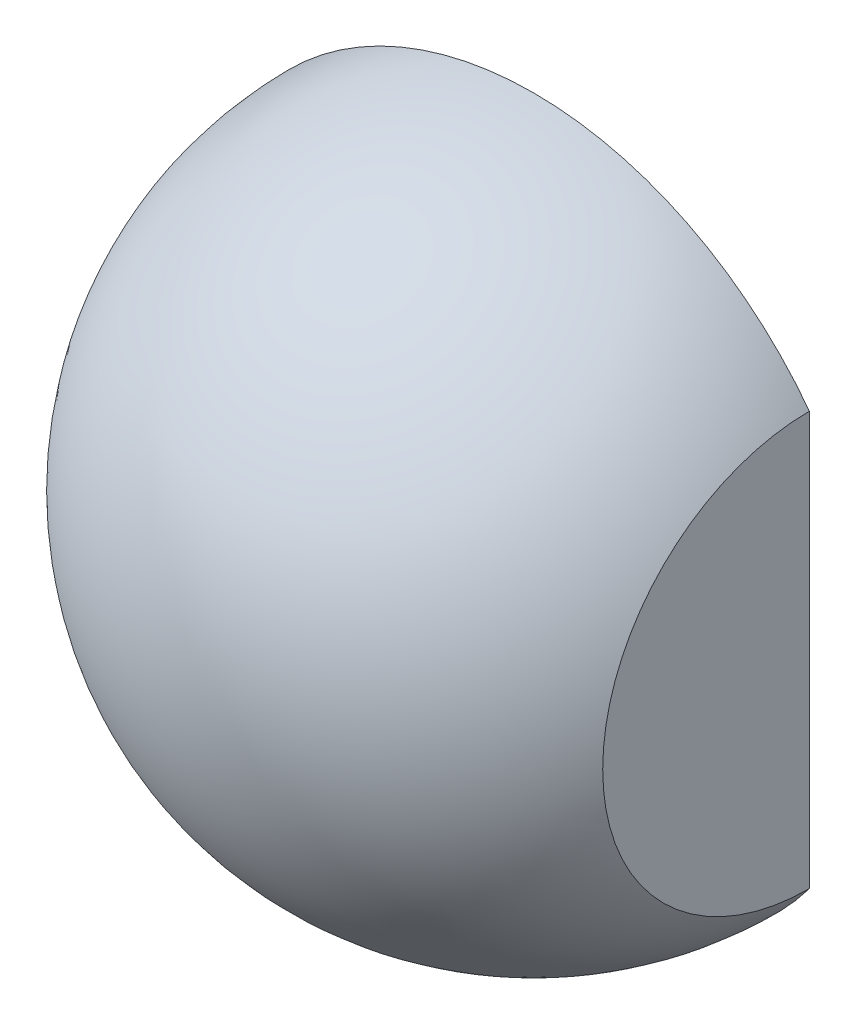
SolidWorks part; units mm, degrees
ref_plane "Front Plane" through (0, 0, 0) normal (0, 0, 1) x (1, 0, 0)
ref_plane "Top Plane" through (0, 0, 0) normal (0, 1, 0) x (1, 0, 0)
ref_plane "Right Plane" through (0, 0, 0) normal (1, 0, 0) x (0, 0, -1)
sketch "Sketch2" plane through (0, 0, 0) normal (0, 0, 1) x (1, 0, 0)
  line L0 (0, 0) -> (0, 30)
  arc A0 (0, 30) -> (0, 0) centre (0, 15) ccw
  dimension "D1" = 30
revolve "Revolve1" add sketch "Sketch2" angle 180 about L0
sketch "Sketch3" plane through (0, 0, 0) normal (0, 0, -1) x (-1, 0, 0)
  line L1 (-12, 34.7081) -> (12, 34.7081)
  line L2 (-12, 34.7081) -> (-12, -4.2692)
  line L3 (-12, -4.2692) -> (12, -4.2692)
  line L4 (12, 34.7081) -> (12, -4.2692)
  line L5 (-28.5307, 39.7997) -> (28.0917, 39.7997)
  line L6 (-28.5307, 39.7997) -> (-28.5307, -12.8723)
  line L7 (-28.5307, -12.8723) -> (28.0917, -12.8723)
  line L8 (28.0917, 39.7997) -> (28.0917, -12.8723)
  dimension "D1" = 12
  dimension "D2" = 12
extrude "Cut-Extrude1" cut sketch "Sketch3" against normal blind 10
sketch "Sketch4" plane through (0, 0, 0) normal (0, 0, -1) x (-1, 0, 0)
  line L0 (0, 0) -> (0, 30) construction
  arc A0 (12, 24) -> (-12, 24) centre (0, 15) ccw construction
  circle A1 centre (0, 15) radius 2.1
  dimension "D1" = 4.2
extrude "Cut-Extrude2" cut sketch "Sketch4" against normal blind 8
equation "\"ž\"=8"
